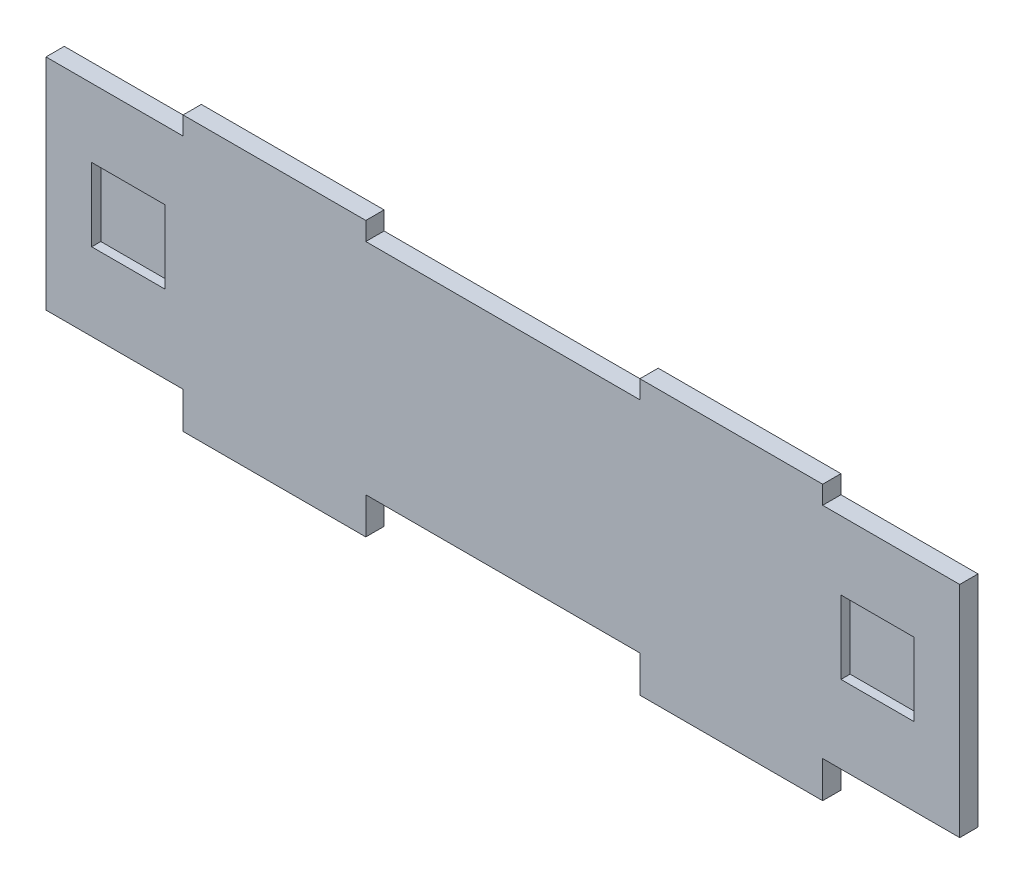
SolidWorks part; units mm, degrees
ref_plane "Front Plane" through (0, 0, 0) normal (0, 0, 1) x (1, 0, 0)
ref_plane "Top Plane" through (0, 0, 0) normal (0, 1, 0) x (1, 0, 0)
ref_plane "Right Plane" through (0, 0, 0) normal (1, 0, 0) x (0, 0, -1)
sketch "Sketch1" plane through (0, 0, 0) normal (0, 0, 1) x (1, 0, 0)
  line L0 (30, 60) -> (70, 60)
  line L1 (30, 0) -> (70, 0)
  line L2 (0, 8) -> (0, 56)
  line L3 (130, 0) -> (170, 0)
  line L4 (200, 8) -> (200, 56)
  line L5 (130, 60) -> (170, 60)
  line L7 (0, 8) -> (30, 8)
  line L8 (30, 0) -> (30, 8)
  line L10 (70, 0) -> (70, 8)
  line L11 (70, 8) -> (130, 8)
  line L12 (130, 0) -> (130, 8)
  line L13 (0, 56) -> (30, 56)
  line L14 (170, 0) -> (170, 8)
  line L15 (170, 8) -> (200, 8)
  line L16 (30, 60) -> (30, 56)
  line L18 (70, 60) -> (70, 56)
  line L19 (70, 56) -> (130, 56)
  line L20 (130, 60) -> (130, 56)
  line L22 (170, 60) -> (170, 56)
  line L23 (170, 56) -> (200, 56)
  dimension "D1" = 60
  dimension "D2" = 200
  dimension "D3" = 30
  dimension "D4" = 8
  dimension "D5" = 8
  dimension "D6" = 8
  dimension "D7" = 40
  dimension "D8" = 40
  dimension "D9" = 30
  dimension "D10" = 4
extrude "Boss-Extrude1" add sketch "Sketch1" along normal blind 4
sketch "Sketch2" plane through (0, 0, 4) normal (0, 0, 1) x (1, 0, 0)
  line L0 (0, 56) -> (0, 8) construction
  line L1 (10, 41) -> (26, 41)
  line L2 (10, 41) -> (10, 25)
  line L3 (10, 25) -> (26, 25)
  line L4 (26, 41) -> (26, 25)
  line L5 (174, 41) -> (190, 41)
  line L6 (174, 41) -> (174, 25)
  line L7 (174, 25) -> (190, 25)
  line L8 (190, 41) -> (190, 25)
  line L9 (200, 8) -> (200, 56) construction
  line L10 (30, 56) -> (0, 56) construction
  point P12 (0, 0)
  point P13 (0, 0)
  dimension "D1" = 16
  dimension "D2" = 16
  dimension "D3" = 16
  dimension "D4" = 16
  dimension "D5" = 10
  dimension "D6" = 10
  dimension "D7" = 15
extrude "Cut-Extrude1" cut sketch "Sketch2" against normal blind 2
